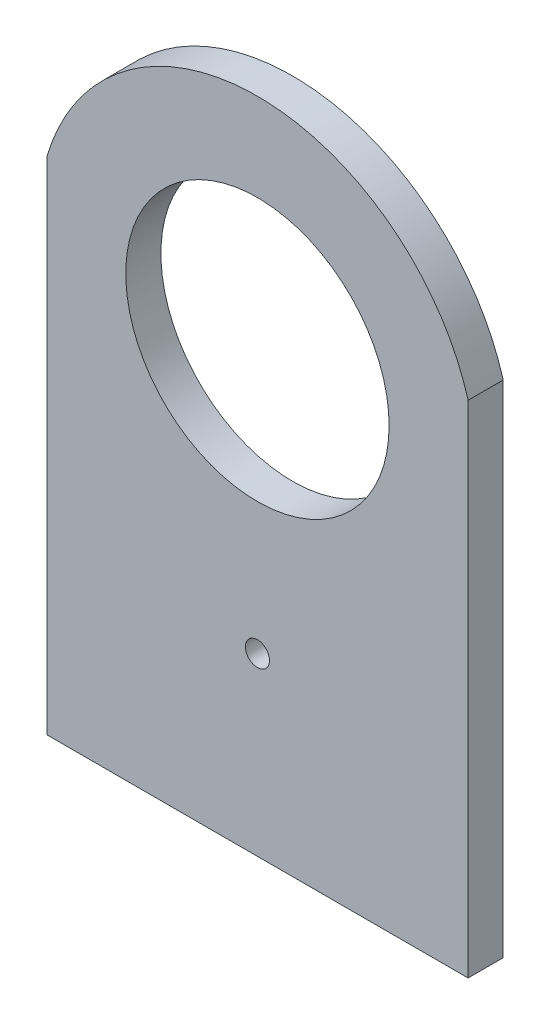
SolidWorks part; units mm, degrees
ref_plane "前视基准面" through (0, 0, 0) normal (0, 0, 1) x (1, 0, 0)
ref_plane "上视基准面" through (0, 0, 0) normal (0, 1, 0) x (1, 0, 0)
ref_plane "右视基准面" through (0, 0, 0) normal (1, 0, 0) x (0, 0, -1)
other "Configuration Table"
sketch "草图1" plane through (0, 0, 0) normal (0, 0, 1) x (1, 0, 0)
  line L0 (0, 0) -> (0, 150.9585) construction
  line L3 (-48, 114) -> (-48, 0)
  line L4 (-48, 0) -> (48, 0)
  line L5 (48, 114) -> (48, 0)
  circle A0 centre (0, 100) radius 30
  arc A2 (48, 114) -> (-48, 114) centre (0, 100) ccw
  dimension "D3" = 60
  dimension "D4" = 50
  dimension "D1" = 96
  dimension "D2" = 100
extrude "凸台-拉伸1" add sketch "草图1" along normal blind 8
sketch "草图2" plane through (0, 0, 0) normal (0, -1, 0) x (1, 0, 0)
  line L0 (-53.8408, 4) -> (58.1589, 4) construction
  line L1 (0, 20.308) -> (0, -17.9139) construction
  line L2 (-48, 8) -> (48, 8) construction
  line L3 (-48, 0) -> (48, 0) construction
  circle A0 centre (35, 4) radius 2.75
  circle A1 centre (-35, 4) radius 2.75
  dimension "D2" = 5.5
  dimension "D1" = 70
extrude "切除-拉伸1" cut sketch "草图2" against normal blind 50
sketch "草图3" plane through (0, 0, 8) normal (0, 0, 1) x (1, 0, 0)
  line L0 (0, 0) -> (0, 95.092) construction
  circle A0 centre (0, 40) radius 2.75
  dimension "D1" = 5.5
  dimension "D2" = 40
extrude "切除-拉伸2" cut sketch "草图3" against normal blind 20
